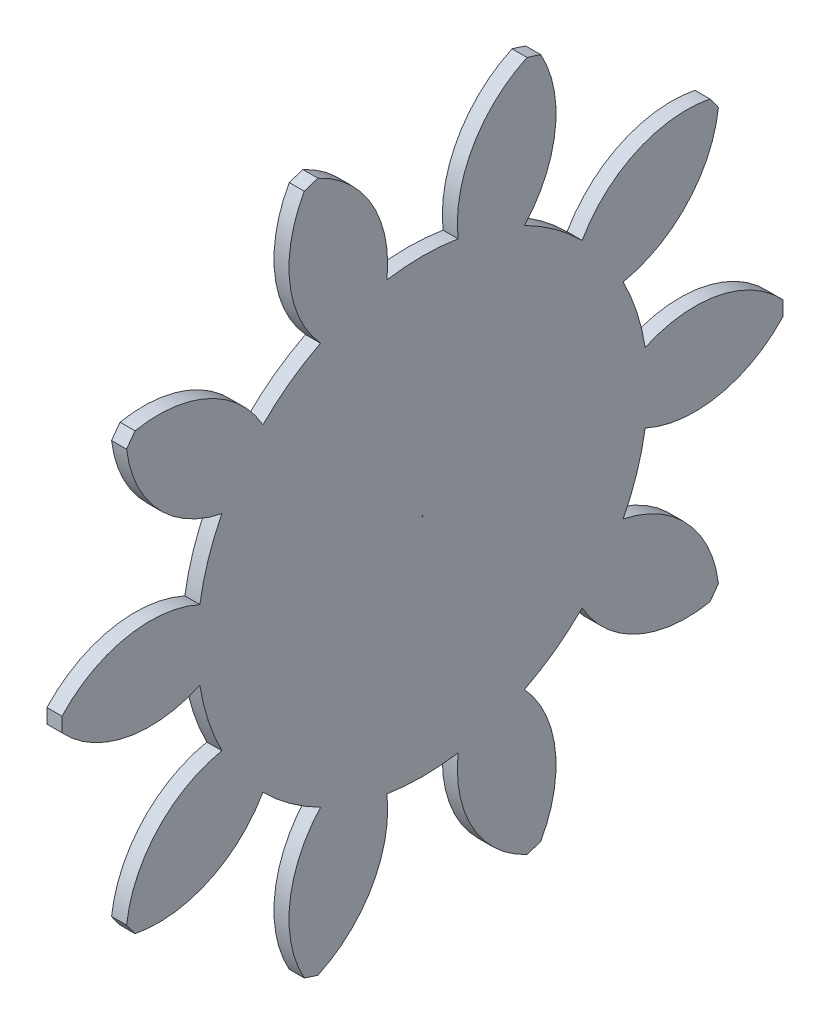
SolidWorks part; units mm, degrees
ref_plane "Plane1" through (0, 0, 0) normal (0, 0, 1) x (1, 0, 0)
ref_plane "Plane2" through (0, 0, 0) normal (0, 1, 0) x (1, 0, 0)
ref_plane "Plane3" through (0, 0, 0) normal (1, 0, 0) x (0, 0, -1)
other "Configuration Table"
sketch "HoldingSke" plane through (0, 0, 0) normal (0, 1, 0) x (1, 0, 0)
  line L0 (0, 0) -> (12.5071, -2.2053)
  line L1 (-15, 0) -> (100, 0) construction
  line L2 (0, 0) -> (-2.1039, 2.3779)
  line L3 (0, 0) -> (-11.863, 4.5341)
  line L4 (0, 0) -> (8.5048, 1.4996)
  line L5 (0, 0) -> (-47.5972, -17.7524)
  line L6 (0, 0) -> (-10.5278, -7.1032)
  line L7 (-2.1039, 2.3779) -> (8.8308, 51.9871)
  line L8 (-76.2, 54.61) -> (-75.184, 54.61)
  line L9 (-71.009, 38.7566) -> (-53.1078, 45.2721)
  line L10 (-76.2, 71.12) -> (104.1128, 71.12)
  line L11 (0, 0) -> (-12.7, 0)
  line L12 (-76.2, 101.6) -> (-74.295, 101.6)
  line L13 (24.9733, 27.94) -> (52.9518, 28.4284)
  line L14 (24.9733, 27.94) -> (24.9746, 27.94)
  line L15 (24.9733, 27.94) -> (100.4006, 29.5858)
  circle A0 centre (0, 0) radius 0.3969
  circle A1 centre (0, 0) radius 38.1
  circle A2 centre (0, 0) radius 38.1
  circle A3 centre (0, 0) radius 0.3969
  dimension "MHD" = 76.2
  dimension "Hub_dia" = 76.2
  dimension "Bore" = 0.7937
  dimension "MBD" = 0.7937
  dimension "Num_teeth" = 10
  dimension "Pitch" = 12.7
  dimension "Overall_len" = 50.8
  dimension "Show_teeth" = 10
  dimension "Thickness" = 12.7
  dimension "OAL" = 50.8001
  dimension "T_dim" = 1.016
  dimension "Ap" = 20
  dimension "H" = 19.05
  dimension "Pitch_radius" = 180.3128
  dimension "Width" = 12.7
  dimension "Backlash" = 1.905
  dimension "Addendum_fac" = 1
  dimension "Dedendum_fac" = 1.25
  dimension "Clearance_fac" = 0.25
  dimension "Dedendum_add" = 0.0013
sketch "BasProSke" plane through (0, 0, 0) normal (0, 1, 0) x (1, 0, 0)
  line L0 (-10, 0) -> (60, 0) construction
  line L1 (0, 0) -> (0, 304.8)
  line L2 (0, 0) -> (12.7, 0)
  line L3 (12.7, 0) -> (12.7, 304.8)
  line L4 (12.7, 304.8) -> (0, 304.8)
  dimension "Thickness" = 12.7
  dimension "Diameter" = 609.6
revolve "Base-Revolve" add sketch "BasProSke" angle 360 about L0
sketch "TooCutSke" plane through (0, 0, 0) normal (1, 0, 0) x (0, 0, -1)
  line L1 (0, 0) -> (0, 107) construction
  line L2 (0, 0) -> (-43.0611, 250.3233) construction
  line L3 (0, 0) -> (-155.3603, 478.1497) construction
  line L4 (-43.0611, 250.3233) -> (-77.6801, 239.0749) construction
  arc A0 (30.0743, 188.1098) -> (-30.0743, 188.1098) centre (0, 0) ccw
  arc A1 (88.4088, 291.7232) -> (-88.4088, 291.7232) centre (0, 0) ccw
  circle A2 centre (0, 0) radius 254 construction
  circle A3 centre (0, 0) radius 238.6819 construction
  arc A4 (-30.0743, 188.1098) -> (-88.4088, 291.7232) centre (-131.0342, 199.4971) ccw
  arc A5 (88.4088, 291.7232) -> (30.0743, 188.1098) centre (131.0342, 199.4971) ccw
  dimension "Root_dia" = 380.9975
  dimension "Overcut_dia" = 609.6508
  dimension "Pitch_dia" = 508
  dimension "Base_dia" = 477.3639
  dimension "Flank_rad" = 101.6
  dimension "Half_ang" = 18
  dimension "Half_CT" = 36.4006
extrude "ToothCut" cut sketch "TooCutSke" along normal through all
fillet "Breaks" [suppressed] radius 1.016
fillet "RootFillets" [suppressed] radius 12.7013
pattern_circular "TeethCuts" count 10 every 36 about axis through (-10, 0, 0) along (1, 0, 0) of "ToothCut", "RootFillets", "Breaks"
sketch "HubNeaOneSke" plane through (0, 0, 0) normal (-1, 0, 0) x (0, 0, 1)
  circle A0 centre (0, 0) radius 38.1
  dimension "Diameter" = 76.2
extrude "HubNearOne" [suppressed] add sketch "HubNeaOneSke" along normal blind 38.1001
sketch "HubNeaBotSke" plane through (0, 0, 0) normal (-1, 0, 0) x (0, 0, 1)
  circle A0 centre (0, 0) radius 38.1
  dimension "Diameter" = 76.2
extrude "HubNearBoth" [suppressed] add sketch "HubNeaBotSke" along normal blind 19.05
ref_plane "FarPln" through (12.7, 0, 0) normal (1, 0, 0) x (0, 0, -1)
sketch "HubFarSke" plane through (12.7, 0, 0) normal (1, 0, 0) x (0, 0, -1)
  circle A0 centre (0, 0) radius 38.1
  dimension "Diameter" = 76.2
extrude "HubFar" [suppressed] add sketch "HubFarSke" along normal blind 19.05
sketch "BorSke" plane through (0, 0, 0) normal (1, 0, 0) x (0, 0, -1)
  circle A0 centre (0, 0) radius 0.3969
  dimension "Diameter" = 0.7937
extrude "Bore" cut sketch "BorSke" along normal mid plane 101.6001
sketch "KeySke" plane through (0, 0, 0) normal (1, 0, 0) x (0, 0, -1)
  line L0 (-0.127, 0) -> (-0.127, 0.6191)
  line L1 (-0.127, 0.6191) -> (0.127, 0.6191)
  line L2 (0.127, 0.6191) -> (0.127, 0)
  line L3 (0, 0) -> (0, 34) construction
  line L4 (-0.127, 0) -> (0.127, 0)
  dimension "Offset" = 0.6191
extrude "Keyway" [suppressed] cut sketch "KeySke" along normal mid plane 101.6001
pattern_circular "Keyway2" [suppressed] count 2 every 90 about axis through (-10, 0, 0) along (1, 0, 0)
equation "' \"Pitch@HoldingSke\" = 4"
equation "' \"Num_teeth@HoldingSke\" = 12"
equation "' \"Ap@HoldingSke\" =  20"
equation "' \"Ap@HoldingSke\" = 20"
equation "' \"Width@HoldingSke\" = 0.5"
equation "' \"Hub_dia@HoldingSke\"= 1"
equation "' \"Hub_dia@HoldingSke\" = 1"
equation "' \"Overall_len@HoldingSke\" = 1.0"
equation "' \"Bore@HoldingSke\" = 0.75"
equation "' \"T_dim@HoldingSke\" = 0.85"
equation "' \"Width@KeySke\" = 0.25"
equation "' \"Show_teeth@HoldingSke\" = 13"
equation "' \"Backlash@HoldingSke\" = 0.009"
equation "' \"Addendum_fac@HoldingSke\" = 1.0"
equation "' \"Dedendum_fac@HoldingSke\" = 1.25"
equation "' \"Dedendum_add@HoldingSke\" = 0.00005"
equation "' \"Clearance_fac@HoldingSke\" = 0.25"
equation "' \"Pitch@HoldingSke\" = 0.5"
equation "' \"Num_teeth@HoldingSke\" = 23"
equation "' \"Show_teeth@HoldingSke\" = 23"
equation "' \"Backlash@HoldingSke\" = 0.0375"
equation "\"Overcut_dia@TooCutSke\" = (\"Num_teeth@HoldingSke\" + 2 * \"Addendum_fac@HoldingSke\") / \"Pitch@HoldingSke\" + 0.002"
equation "\"Pitch_dia@TooCutSke\" = \"Num_teeth@HoldingSke\" / \"Pitch@HoldingSke\""
equation "\"Base_dia@TooCutSke\" = \"Num_teeth@HoldingSke\" / \"Pitch@HoldingSke\" * cos((\"Ap@HoldingSke\"  * 3.14159265 / 180))"
equation "\"Root_dia@TooCutSke\" = (\"Num_teeth@HoldingSke\" + 2) / \"Pitch@HoldingSke\" - 2 * (\"Addendum_fac@HoldingSke\" + \"Dedendum_fac@HoldingSke\") / \"Pitch@HoldingSke\" - \"Dedendum_add@HoldingSke\" * 2"
equation "\"Half_ang@TooCutSke\" = 180 / \"Num_teeth@HoldingSke\""
equation "\"Half_CT@TooCutSke\" = \"Num_teeth@HoldingSke\" / \"Pitch@HoldingSke\" * sin((3.14159265 / 2 / \"Num_teeth@HoldingSke\")) / 2 - 7 * \"Backlash@HoldingSke\" / 4"
equation "\"Flank_rad@TooCutSke\" = \"Num_teeth@HoldingSke\" / \"Pitch@HoldingSke\" / 5"
equation "\"Radius@RootFillets\" = \"Clearance_fac@HoldingSke\" / \"Pitch@HoldingSke\" + \"Dedendum_add@HoldingSke\""
equation "\"Break_rad@Breaks\" = 0.02 / \"Pitch@HoldingSke\""
equation "\"Thickness@HoldingSke\" = \"Width@HoldingSke\""
equation "\"OAL@HoldingSke\" = \"Thickness@HoldingSke\""
equation "\"MHD@HoldingSke\" = (\"Num_teeth@HoldingSke\" + 2) / \"Pitch@HoldingSke\" - 2 * (\"Addendum_fac@HoldingSke\" + \"Dedendum_fac@HoldingSke\")  / \"Pitch@HoldingSke\" - \"Dedendum_add@HoldingSke\" * 2"
equation "\"MBD@HoldingSke\" = (\"Num_teeth@HoldingSke\" + 2) / \"Pitch@HoldingSke\" - 2 * (\"Addendum_fac@HoldingSke\" + \"Dedendum_fac@HoldingSke\")  / \"Pitch@HoldingSke\" - \"Dedendum_add@HoldingSke\" * 2 - 0.002"
equation "\"MHD@HoldingSke\" = ((sgn( \"MHD@HoldingSke\" - \"Hub_dia@HoldingSke\" )-1)*( \"MHD@HoldingSke\" - \"Hub_dia@HoldingSke\" ))/-2+ \"Hub_dia@HoldingSke\""
equation "\"MBD@HoldingSke\" = ((sgn( \"MBD@HoldingSke\" - \"Bore@HoldingSke\" )-1)*( \"MBD@HoldingSke\" - \"Bore@HoldingSke\" ))/-2+ \"Bore@HoldingSke\""
equation "\"OAL@HoldingSke\" = ((sgn( \"OAL@HoldingSke\" - \"Overall_len@HoldingSke\" )+1)*( \"OAL@HoldingSke\" - \"Overall_len@HoldingSke\" ))/2 + \"Overall_len@HoldingSke\" + 0.000002"
equation "\"Num_teeth@TeethCuts\" = int( \"Show_teeth@HoldingSke\" ) + 1"
equation "\"Num_teeth@TeethCuts\" = ((sgn( \"Num_teeth@TeethCuts\" - \"Num_teeth@HoldingSke\" )-1)*( \"Num_teeth@TeethCuts\" - \"Num_teeth@HoldingSke\" ))/-2+ \"Num_teeth@HoldingSke\""
equation "\"Num_teeth@TeethCuts\" = ((sgn( \"Num_teeth@TeethCuts\" - 2.0)+1)*( \"Num_teeth@TeethCuts\" - 2.0))/2 +2.0"
equation "\"Angle@TeethCuts\" = 360.0 / \"Num_teeth@HoldingSke\""
equation "\"Diameter@BasProSke\" = (\"Num_teeth@HoldingSke\" + 2 * \"Addendum_fac@HoldingSke\") / \"Pitch@HoldingSke\""
equation "\"Thickness@BasProSke\"  = \"Thickness@HoldingSke\""
equation "' \"Fillet_rad@BasProSke\" =  \"Thickness@HoldingSke\" * 0.05"
equation "' \"Fillet_rad@BasProSke\" = \"Thickness@HoldingSke\" * 0.05"
equation "\"MHD@HoldingSke\" = ((sgn( \"MHD@HoldingSke\" - \"Root_dia@TooCutSke\" )-1)*( \"MHD@HoldingSke\" - \"Root_dia@TooCutSke\" ))/-2+ \"Root_dia@TooCutSke\""
equation "\"Diameter@HubNeaOneSke\" = \"MHD@HoldingSke\""
equation "\"Length@HubNearOne\" = \"OAL@HoldingSke\" - \"Thickness@BasProSke\""
equation "\"Diameter@HubNeaBotSke\" = \"MHD@HoldingSke\""
equation "\"Length@HubNearBoth\" = ( \"OAL@HoldingSke\" - \"Thickness@BasProSke\" ) / 2.0"
equation "\"Thickness@FarPln\" = \"Thickness@BasProSke\""
equation "\"Diameter@HubFarSke\" = \"MHD@HoldingSke\""
equation "\"Length@HubFar\" = ( \"OAL@HoldingSke\" - \"Thickness@BasProSke\" ) / 2.0"
equation "\"Diameter@BorSke\" = \"MBD@HoldingSke\""
equation "\"D1@Bore\" = \"OAL@HoldingSke\" * 2.0"
equation "\"D1@Keyway\" = \"OAL@HoldingSke\" * 2.0"
equation "\"Offset@KeySke\" = \"T_dim@HoldingSke\" - \"MBD@HoldingSke\" / 2.0"
